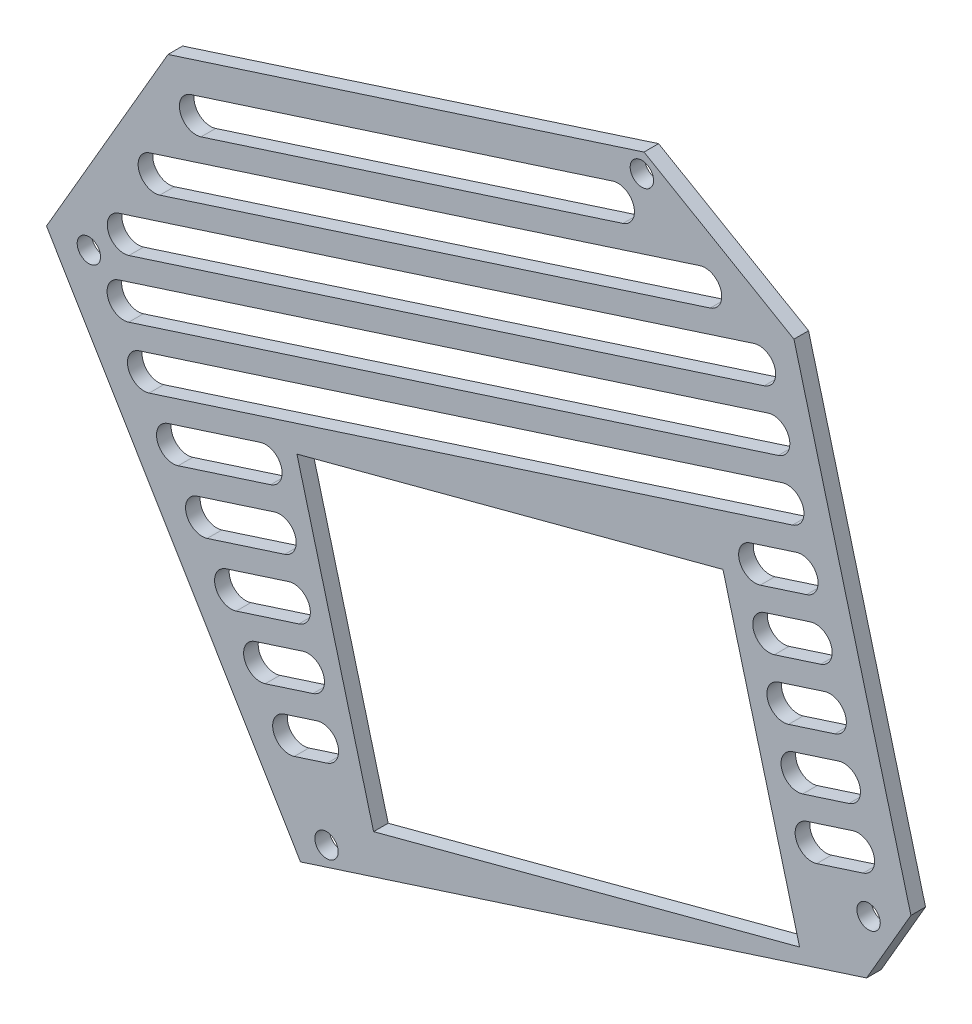
SolidWorks part; units mm, degrees
ref_plane "Front Plane" through (0, 0, 0) normal (0, 0, 1) x (1, 0, 0)
ref_plane "Top Plane" through (0, 0, 0) normal (0, 1, 0) x (1, 0, 0)
ref_plane "Right Plane" through (0, 0, 0) normal (1, 0, 0) x (0, 0, -1)
sketch "Sketch1" plane through (0, 0, 0) normal (0, 0, 1) x (1, 0, 0)
  line L0 (31.4743, 21.3475) -> (89.8136, 36.8354)
  line L1 (31.4743, 21.3475) -> (20.9796, 60.8781)
  line L2 (89.8136, 36.8354) -> (79.3189, 76.3661)
  line L3 (20.9796, 60.8781) -> (79.3189, 76.3661)
  line L4 (27.4247, 20.2724) -> (93.5347, 37.8233) construction
  line L5 (86.7805, 44.363) -> (88.6418, 37.3521) construction
  line L6 (78.609, 75.143) -> (21.8743, 60.081) construction
  line L7 (21.4671, 12.7573) -> (98.9866, 37.7475)
  line L8 (98.9866, 37.7475) -> (108.6061, 54.3208)
  line L9 (108.6061, 54.3208) -> (91.5263, 118.6564)
  line L10 (91.5263, 118.6564) -> (69.6744, 131.3398)
  line L11 (69.6744, 131.3398) -> (5.1354, 110.5341)
  line L12 (5.1354, 110.5341) -> (-15.6687, 74.6914)
  line L13 (-15.6687, 74.6914) -> (21.4671, 12.7573)
  line L14 (21.4671, 12.7573) -> (98.9866, 37.7475)
  line L15 (98.9866, 37.7475) -> (108.6061, 54.3208)
  line L16 (108.6061, 54.3208) -> (91.5263, 118.6564)
  line L17 (91.5263, 118.6564) -> (69.6744, 131.3398)
  line L18 (69.6744, 131.3398) -> (5.1354, 110.5341)
  line L19 (5.1354, 110.5341) -> (-15.6687, 74.6914)
  line L20 (-15.6687, 74.6914) -> (21.4671, 12.7573)
  circle A0 centre (25.0329, 16.5335) radius 1.6
  circle A1 centre (-7.5135, 70.8134) radius 1.6
  circle A2 centre (68.2128, 117.7351) radius 1.6
  dimension "D4" = 3.2
  dimension "D2" = 1
  dimension "D3" = 1
  dimension "D1" = 0
extrude "Boss-Extrude1" add sketch "Sketch1" along normal blind 2
sketch "Sketch2" plane through (0, 0, 2) normal (0, 0, 1) x (1, 0, 0)
  line L0 (69.4678, 119.8973) -> (101.2706, 101.4381) construction
  line L1 (67.4458, 120.1146) -> (6.9762, 100.6208) construction
  line L2 (1.3958, 96.123) -> (-42.1211, 21.1492) construction
  line L3 (68.5051, 120.4561) -> (89.0395, 108.5374)
  line L4 (68.5051, 120.4561) -> (3.3227, 99.443)
  line L5 (3.3227, 99.443) -> (-13.3186, 70.7721)
  line L6 (106.847, 41.4609) -> (86.8841, 116.6562) construction
  line L7 (105.0565, 48.2052) -> (89.0395, 108.5374)
  line L15 (-15.6687, 74.6914) -> (21.4671, 12.7573)
  line L16 (21.4671, 12.7573) -> (98.9866, 37.7475)
  line L17 (98.9866, 37.7475) -> (108.6061, 54.3208)
  line L18 (108.6061, 54.3208) -> (91.5263, 118.6564)
  line L19 (91.5263, 118.6564) -> (69.6744, 131.3398)
  line L20 (69.6744, 131.3398) -> (5.1354, 110.5341)
  line L21 (5.1354, 110.5341) -> (-15.6687, 74.6914)
  line L22 (-15.6687, 74.6914) -> (-13.3186, 70.7721)
  line L24 (105.0565, 48.2052) -> (108.6061, 54.3208)
  line L25 (108.6061, 54.3208) -> (91.5263, 118.6564)
  line L26 (91.5263, 118.6564) -> (69.6744, 131.3398)
  line L27 (69.6744, 131.3398) -> (5.1354, 110.5341)
  line L28 (5.1354, 110.5341) -> (-15.6687, 74.6914)
  point P3 (68.4297, 120.4999)
  point P8 (3.3762, 99.5351)
  point P10 (4.0593, 99.5351)
  point P13 (68.2335, 120.4999)
  dimension "D1" = 0
extrude "Cut-Extrude1" cut sketch "Sketch2" against normal blind 2
sketch "Sketch3" plane through (0, 0, 2) normal (0, 0, 1) x (1, 0, 0)
  line L0 (7.1532, 94.0901) -> (64.927, 112.7148) construction
  line L1 (6.4567, 96.2506) -> (64.2305, 114.8753)
  line L2 (7.8497, 91.9296) -> (65.6235, 110.5543)
  line L3 (1.5041, 84.3573) -> (76.8812, 108.6569) construction
  line L4 (0.8076, 86.5178) -> (76.1847, 110.8174)
  line L5 (2.2006, 82.1968) -> (77.5777, 106.4964)
  line L6 (-2.7227, 75.0831) -> (84.2681, 103.1267) construction
  line L7 (-3.4192, 77.2436) -> (83.5716, 105.2872)
  line L8 (-2.0262, 72.9226) -> (84.9646, 100.9662)
  line L9 (-2.7525, 67.1619) -> (86.2029, 95.8388) construction
  line L10 (-3.449, 69.3224) -> (85.5064, 97.9993)
  line L11 (-2.056, 65.0014) -> (86.8993, 93.6783)
  line L12 (3.3227, 99.443) -> (68.5051, 120.4561) construction
  line L13 (0.045, 60.1521) -> (88.1376, 88.5509) construction
  line L14 (-0.6515, 62.3126) -> (87.4412, 90.7114)
  line L15 (0.7415, 57.9916) -> (88.8341, 86.3904)
  line L16 (83.7345, 79.2198) -> (90.0724, 81.263) construction
  line L17 (83.038, 81.3803) -> (89.376, 83.4235)
  line L18 (84.431, 77.0593) -> (90.7689, 79.1025)
  line L19 (4.0204, 53.5221) -> (16.6762, 57.602) construction
  line L20 (3.3239, 55.6826) -> (15.9797, 59.7625)
  line L21 (4.7169, 51.3616) -> (17.3727, 55.4415)
  line L22 (7.9958, 46.892) -> (18.611, 50.3141) construction
  line L23 (7.2993, 49.0526) -> (17.9145, 52.4746)
  line L24 (8.6923, 44.7315) -> (19.3075, 48.1536)
  line L25 (11.9712, 40.262) -> (20.5458, 43.0262) construction
  line L26 (11.2747, 42.4225) -> (19.8493, 45.1867)
  line L27 (12.6677, 38.1015) -> (21.2423, 40.8657)
  line L28 (15.9466, 33.632) -> (22.4806, 35.7383) construction
  line L29 (15.2501, 35.7925) -> (21.7841, 37.8989)
  line L30 (16.6431, 31.4714) -> (23.1771, 33.5778)
  line L31 (19.922, 27.0019) -> (24.4154, 28.4505) construction
  line L32 (19.2255, 29.1624) -> (23.7189, 30.611)
  line L33 (20.6184, 24.8414) -> (25.1118, 26.29)
  line L34 (-13.3186, 70.7721) -> (3.3227, 99.443) construction
  line L37 (85.6693, 71.932) -> (92.0072, 73.9751) construction
  line L38 (84.9728, 74.0925) -> (91.3107, 76.1357)
  line L39 (86.3658, 69.7714) -> (92.7037, 71.8146)
  line L40 (87.6041, 64.6441) -> (93.942, 66.6873) construction
  line L41 (86.9076, 66.8046) -> (93.2455, 68.8478)
  line L42 (88.3006, 62.4836) -> (94.6385, 64.5268)
  line L43 (89.5389, 57.3562) -> (95.8768, 59.3994) construction
  line L44 (88.8424, 59.5167) -> (95.1803, 61.5599)
  line L45 (90.2354, 55.1957) -> (96.5733, 57.2389)
  line L46 (91.4737, 50.0683) -> (97.8116, 52.1115) construction
  line L47 (90.7772, 52.2288) -> (97.1151, 54.272)
  line L48 (92.1702, 47.9078) -> (98.5081, 49.951)
  line L52 (-13.3186, 70.7721) -> (21.4671, 12.7573) construction
  line L53 (20.9796, 60.8781) -> (31.4743, 21.3475) construction
  line L54 (89.8136, 36.8354) -> (79.3189, 76.3661) construction
  line L56 (89.0395, 108.5374) -> (105.0565, 48.2052) construction
  line L57 (102.1975, 58.9743) -> (86.6018, 117.7193) construction
  line L58 (68.5051, 120.4561) -> (89.0395, 108.5374) construction
  arc A0 (6.4567, 96.2506) -> (7.8497, 91.9296) centre (7.1532, 94.0901) ccw
  arc A1 (65.6235, 110.5543) -> (64.2305, 114.8753) centre (64.927, 112.7148) ccw
  arc A2 (0.8076, 86.5178) -> (2.2006, 82.1968) centre (1.5041, 84.3573) ccw
  arc A3 (77.5777, 106.4964) -> (76.1847, 110.8174) centre (76.8812, 108.6569) ccw
  arc A4 (-3.4192, 77.2436) -> (-2.0262, 72.9226) centre (-2.7227, 75.0831) ccw
  arc A5 (84.9646, 100.9662) -> (83.5716, 105.2872) centre (84.2681, 103.1267) ccw
  arc A6 (-3.449, 69.3224) -> (-2.056, 65.0014) centre (-2.7525, 67.1619) ccw
  arc A7 (86.8993, 93.6783) -> (85.5064, 97.9993) centre (86.2029, 95.8388) ccw
  arc A8 (-0.6515, 62.3126) -> (0.7415, 57.9916) centre (0.045, 60.1521) ccw
  arc A9 (88.8341, 86.3904) -> (87.4412, 90.7114) centre (88.1376, 88.5509) ccw
  arc A10 (83.038, 81.3803) -> (84.431, 77.0593) centre (83.7345, 79.2198) ccw
  arc A11 (90.7689, 79.1025) -> (89.376, 83.4235) centre (90.0724, 81.263) ccw
  arc A12 (3.3239, 55.6826) -> (4.7169, 51.3616) centre (4.0204, 53.5221) ccw
  arc A13 (17.3727, 55.4415) -> (15.9797, 59.7625) centre (16.6762, 57.602) ccw
  arc A14 (7.2993, 49.0526) -> (8.6923, 44.7315) centre (7.9958, 46.892) ccw
  arc A15 (19.3075, 48.1536) -> (17.9145, 52.4746) centre (18.611, 50.3141) ccw
  arc A16 (11.2747, 42.4225) -> (12.6677, 38.1015) centre (11.9712, 40.262) ccw
  arc A17 (21.2423, 40.8657) -> (19.8493, 45.1867) centre (20.5458, 43.0262) ccw
  arc A18 (15.2501, 35.7925) -> (16.6431, 31.4714) centre (15.9466, 33.632) ccw
  arc A19 (23.1771, 33.5778) -> (21.7841, 37.8989) centre (22.4806, 35.7383) ccw
  arc A20 (19.2255, 29.1624) -> (20.6184, 24.8414) centre (19.922, 27.0019) ccw
  arc A21 (25.1118, 26.29) -> (23.7189, 30.611) centre (24.4154, 28.4505) ccw
  arc A24 (84.9728, 74.0925) -> (86.3658, 69.7714) centre (85.6693, 71.932) ccw
  arc A25 (92.7037, 71.8146) -> (91.3107, 76.1357) centre (92.0072, 73.9751) ccw
  arc A26 (86.9076, 66.8046) -> (88.3006, 62.4836) centre (87.6041, 64.6441) ccw
  arc A27 (94.6385, 64.5268) -> (93.2455, 68.8478) centre (93.942, 66.6873) ccw
  arc A28 (88.8424, 59.5167) -> (90.2354, 55.1957) centre (89.5389, 57.3562) ccw
  arc A29 (96.5733, 57.2389) -> (95.1803, 61.5599) centre (95.8768, 59.3994) ccw
  arc A30 (90.7772, 52.2288) -> (92.1702, 47.9078) centre (91.4737, 50.0683) ccw
  arc A31 (98.5081, 49.951) -> (97.1151, 54.272) centre (97.8116, 52.1115) ccw
  circle A34 centre (68.2128, 117.7351) radius 1.6 construction
  circle A35 centre (-7.5135, 70.8134) radius 2.5 construction
  circle A36 centre (99.2597, 45.1903) radius 1.6 construction
  circle A37 centre (99.2597, 45.1903) radius 1.6
  point P2 (36.0401, 103.4025)
  point P7 (39.1926, 96.5071)
  point P14 (40.7727, 89.1049)
  point P21 (41.7252, 81.5003)
  point P32 (44.0913, 74.3515)
  point P39 (86.9035, 80.2414)
  point P44 (10.3483, 55.562)
  point P51 (13.3034, 48.6031)
  point P58 (16.2585, 41.6441)
  point P65 (19.2136, 34.6852)
  point P72 (22.1687, 27.7262)
  point P79 (96.943, 43.4798)
  point P86 (88.8383, 72.9536)
  point P93 (90.7731, 65.6657)
  point P100 (92.7079, 58.3778)
  point P107 (94.6426, 51.0899)
  point P121 (22.7934, 20.0064)
  point P122 (26.5114, 25.2121)
  dimension "D1" = 2.27
  dimension "D2" = 7.53
  dimension "D3" = 7.53
  dimension "D4" = 7.53
  dimension "D5" = 7.53
  dimension "D6" = 7.53
  dimension "D7" = 4
  dimension "D8" = 7.53
  dimension "D9" = 7.53
  dimension "D10" = 7.53
  dimension "D11" = 7.53
  dimension "D13" = 6
  dimension "D14" = 6
  dimension "D15" = 7
  dimension "D16" = 6
  dimension "D17" = 6
  dimension "D18" = 6
  dimension "D19" = 6
  dimension "D20" = 6
  dimension "D21" = 6
  dimension "D22" = 5
  dimension "D23" = 5
  dimension "D24" = 5
  dimension "D25" = 5
  dimension "D26" = 5
  dimension "D28" = 5
  dimension "D29" = 5
  dimension "D30" = 5
  dimension "D31" = 5
  dimension "D32" = 5
  dimension "D34" = 6
  dimension "D35" = 6
  dimension "D36" = 6
  dimension "D37" = 6
  dimension "D38" = 6
  dimension "D39" = 6
  dimension "D40" = 6
  dimension "D41" = 6
  dimension "D42" = 6
  dimension "D43" = 6
  dimension "D44" = 6
extrude "Cut-Extrude2" cut sketch "Sketch3" against normal blind 2
